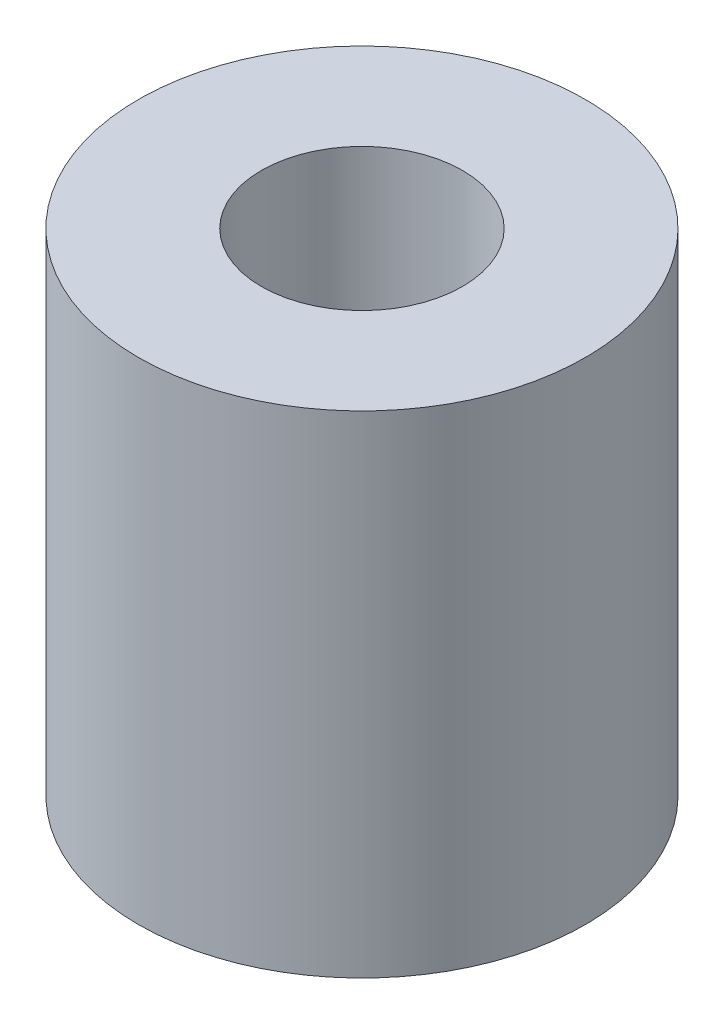
SolidWorks part; units mm, degrees
ref_plane "Front Plane" through (0, 0, 0) normal (0, 0, 1) x (1, 0, 0)
ref_plane "Top Plane" through (0, 0, 0) normal (0, 1, 0) x (1, 0, 0)
ref_plane "Right Plane" through (0, 0, 0) normal (1, 0, 0) x (0, 0, -1)
sketch "Sketch1" plane through (0, 0, 0) normal (0, 1, 0) x (1, 0, 0)
  circle A0 centre (0, 0) radius 10
  point P3 (0, 0)
  dimension "D1" = 20
extrude "Boss-Extrude1" add sketch "Sketch1" along normal blind 21.976
sketch "Sketch2" plane through (0, 21.976, 0) normal (0, 1, 0) x (1, 0, 0)
  circle A0 centre (0, 0) radius 4.5
  point P0 (0, 0)
  dimension "D1" = 9
extrude "Cut-Extrude1" cut sketch "Sketch2" against normal through all contours A0
